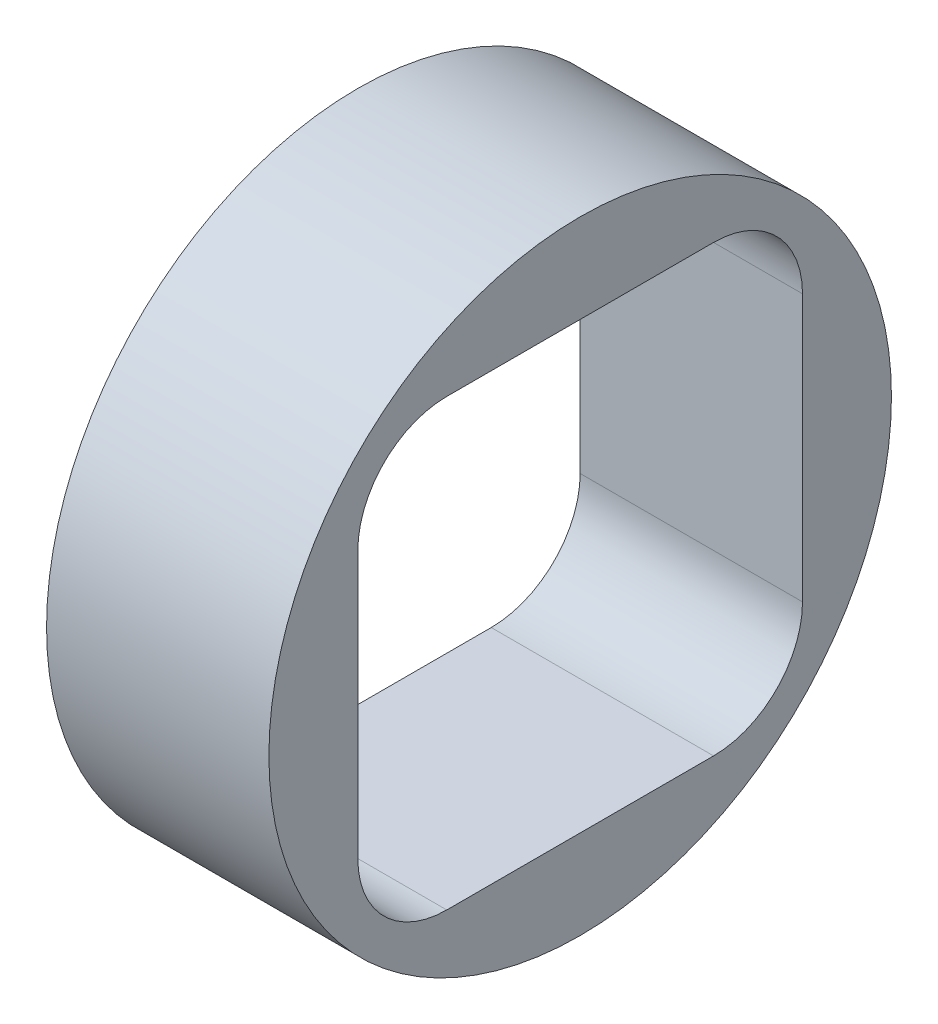
SolidWorks part; units mm, degrees
material "ABS"
ref_plane "Front Plane" through (0, 0, 0) normal (0, 0, 1) x (1, 0, 0)
ref_plane "Top Plane" through (0, 0, 0) normal (0, 1, 0) x (1, 0, 0)
ref_plane "Right Plane" through (0, 0, 0) normal (1, 0, 0) x (0, 0, -1)
sketch "Sketch1" plane through (0, 0, 0) normal (1, 0, 0) x (0, 0, -1)
  line L1 (1.905, -3.175) -> (-1.905, -3.175)
  line L2 (3.175, -1.905) -> (3.175, 1.905)
  line L3 (1.905, 3.175) -> (-1.905, 3.175)
  line L4 (-3.175, -1.905) -> (-3.175, 1.905)
  line L5 (3.175, -3.175) -> (-3.175, 3.175) construction
  line L6 (3.175, 3.175) -> (-3.175, -3.175) construction
  circle A0 centre (0, 0) radius 4.445
  arc A1 (1.905, -3.175) -> (3.175, -1.905) centre (1.905, -1.905) ccw
  arc A2 (1.905, 3.175) -> (3.175, 1.905) centre (1.905, 1.905) cw
  arc A3 (-1.905, -3.175) -> (-3.175, -1.905) centre (-1.905, -1.905) cw
  arc A4 (-1.905, 3.175) -> (-3.175, 1.905) centre (-1.905, 1.905) ccw
  point P0 (0, 0)
  dimension "D2" = 8.89
  dimension "D3" = 1.27
  dimension "D1" = 6.35
sketch "Sketch4" [suppressed] plane through (0, 0, 0) normal (1, 0, 0) x (0, 0, -1)
  line L0 (1.905, 3.175) -> (-1.905, 3.175) construction
  line L1 (-3.175, -1.905) -> (-3.175, 1.905) construction
  line L2 (1.905, -3.175) -> (-1.905, -3.175) construction
  line L3 (3.175, -1.905) -> (3.175, 1.905) construction
  line L4 (1.905, 3.175) -> (-1.905, 3.175)
  line L5 (-3.175, -1.905) -> (-3.175, 1.905)
  line L6 (1.905, -3.175) -> (-1.905, -3.175)
  line L7 (3.175, -1.905) -> (3.175, 1.905)
  arc A0 (-1.905, 3.175) -> (-3.175, 1.905) centre (-1.905, 1.905) ccw construction
  arc A1 (-3.175, -1.905) -> (-1.905, -3.175) centre (-1.905, -1.905) ccw construction
  arc A2 (1.905, -3.175) -> (3.175, -1.905) centre (1.905, -1.905) ccw construction
  arc A3 (3.175, 1.905) -> (1.905, 3.175) centre (1.905, 1.905) ccw construction
  circle A4 centre (0, 0) radius 4.445 construction
  arc A5 (-1.905, 3.175) -> (-3.175, 1.905) centre (-1.905, 1.905) ccw
  arc A6 (-3.175, -1.905) -> (-1.905, -3.175) centre (-1.905, -1.905) ccw
  arc A7 (1.905, -3.175) -> (3.175, -1.905) centre (1.905, -1.905) ccw
  arc A8 (3.175, 1.905) -> (1.905, 3.175) centre (1.905, 1.905) ccw
  circle A9 centre (0, 0) radius 4.445
extrude "Boss-Extrude3" [suppressed] add sketch "Sketch4" along normal blind 6.35
sketch "Sketch3" [suppressed] plane through (0, 0, 0) normal (1, 0, 0) x (0, 0, -1)
  line L0 (1.905, 3.175) -> (-1.905, 3.175) construction
  line L1 (-3.175, -1.905) -> (-3.175, 1.905) construction
  line L2 (1.905, -3.175) -> (-1.905, -3.175) construction
  line L3 (3.175, -1.905) -> (3.175, 1.905) construction
  line L4 (1.905, 3.175) -> (-1.905, 3.175)
  line L5 (-3.175, -1.905) -> (-3.175, 1.905)
  line L6 (1.905, -3.175) -> (-1.905, -3.175)
  line L7 (3.175, -1.905) -> (3.175, 1.905)
  arc A0 (-1.905, 3.175) -> (-3.175, 1.905) centre (-1.905, 1.905) ccw construction
  arc A1 (-3.175, -1.905) -> (-1.905, -3.175) centre (-1.905, -1.905) ccw construction
  arc A2 (1.905, -3.175) -> (3.175, -1.905) centre (1.905, -1.905) ccw construction
  arc A3 (3.175, 1.905) -> (1.905, 3.175) centre (1.905, 1.905) ccw construction
  circle A4 centre (0, 0) radius 4.445 construction
  arc A5 (-1.905, 3.175) -> (-3.175, 1.905) centre (-1.905, 1.905) ccw
  arc A6 (-3.175, -1.905) -> (-1.905, -3.175) centre (-1.905, -1.905) ccw
  arc A7 (1.905, -3.175) -> (3.175, -1.905) centre (1.905, -1.905) ccw
  arc A8 (3.175, 1.905) -> (1.905, 3.175) centre (1.905, 1.905) ccw
  circle A9 centre (0, 0) radius 4.445
extrude "Boss-Extrude2" [suppressed] add sketch "Sketch3" along normal blind 12.7
sketch "Sketch2" plane through (0, 0, 0) normal (1, 0, 0) x (0, 0, -1)
  line L0 (1.905, 3.175) -> (-1.905, 3.175) construction
  line L1 (-3.175, -1.905) -> (-3.175, 1.905) construction
  line L2 (1.905, -3.175) -> (-1.905, -3.175) construction
  line L3 (3.175, -1.905) -> (3.175, 1.905) construction
  line L4 (1.905, 3.175) -> (-1.905, 3.175)
  line L5 (-3.175, -1.905) -> (-3.175, 1.905)
  line L6 (1.905, -3.175) -> (-1.905, -3.175)
  line L7 (3.175, -1.905) -> (3.175, 1.905)
  arc A0 (-1.905, 3.175) -> (-3.175, 1.905) centre (-1.905, 1.905) ccw construction
  arc A1 (-3.175, -1.905) -> (-1.905, -3.175) centre (-1.905, -1.905) ccw construction
  arc A2 (1.905, -3.175) -> (3.175, -1.905) centre (1.905, -1.905) ccw construction
  arc A3 (3.175, 1.905) -> (1.905, 3.175) centre (1.905, 1.905) ccw construction
  circle A4 centre (0, 0) radius 4.445 construction
  arc A5 (-1.905, 3.175) -> (-3.175, 1.905) centre (-1.905, 1.905) ccw
  arc A6 (-3.175, -1.905) -> (-1.905, -3.175) centre (-1.905, -1.905) ccw
  arc A7 (1.905, -3.175) -> (3.175, -1.905) centre (1.905, -1.905) ccw
  arc A8 (3.175, 1.905) -> (1.905, 3.175) centre (1.905, 1.905) ccw
  circle A9 centre (0, 0) radius 4.445
extrude "Boss-Extrude1" add sketch "Sketch2" along normal blind 3.175
